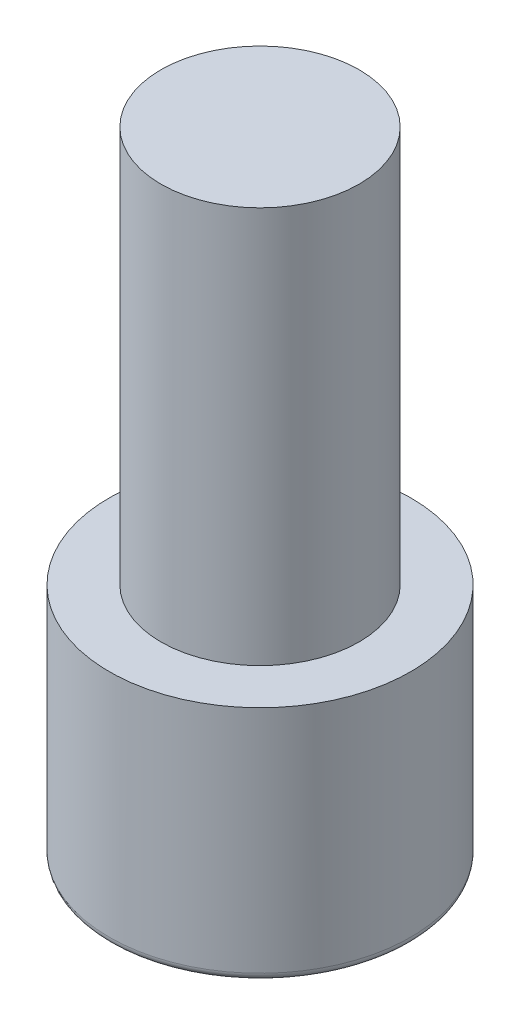
SolidWorks part; units mm, degrees
material "ABS"
ref_plane "Front Plane" through (0, 0, 0) normal (0, 0, 1) x (1, 0, 0)
ref_plane "Top Plane" through (0, 0, 0) normal (0, 1, 0) x (1, 0, 0)
ref_plane "Right Plane" through (0, 0, 0) normal (1, 0, 0) x (0, 0, -1)
sketch "Sketch1" plane through (0, 0, 0) normal (0, 1, 0) x (1, 0, 0)
  line L0 (0, 0) -> (4.826, 0) construction
  line L1 (0, 0) -> (-4.826, 0) construction
  line L2 (0, 0) -> (0, 4.826) construction
  line L3 (0, 0) -> (0, -4.826) construction
  circle A0 centre (0, 0) radius 4.826
  dimension "D1" = 9.652
extrude "Boss-Extrude1" add sketch "Sketch1" along normal blind 7.62
sketch "Sketch2" plane through (0, 7.62, 0) normal (0, 1, 0) x (1, 0, 0)
  circle A0 centre (0, 0) radius 3.175
  dimension "D1" = 6.35
extrude "Boss-Extrude2" add sketch "Sketch2" along normal blind 12.7
fillet "Fillet1" radius 0.254 1 edges at (0, 0, 4.826)
